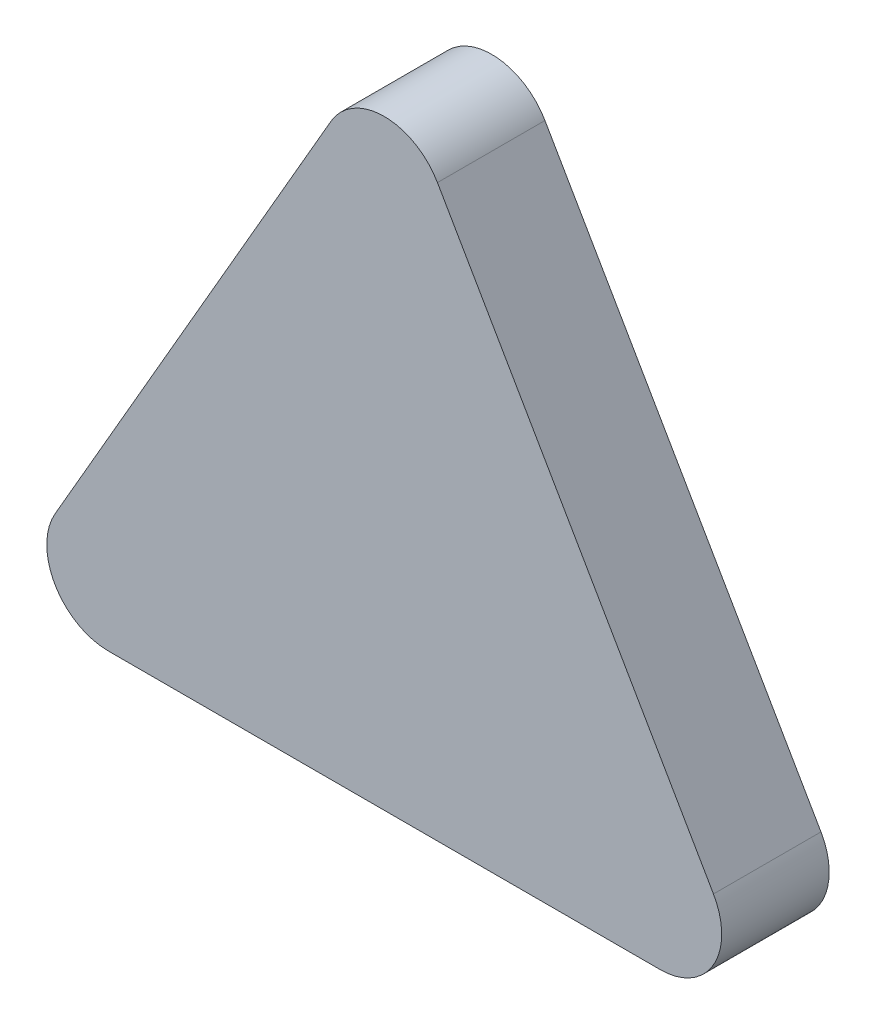
SolidWorks part; units mm, degrees
ref_plane "Plan de face" through (0, 0, 0) normal (0, 0, 1) x (1, 0, 0)
ref_plane "Plan de dessus" through (0, 0, 0) normal (0, 1, 0) x (1, 0, 0)
ref_plane "Plan de droite" through (0, 0, 0) normal (1, 0, 0) x (0, 0, -1)
sketch "Esquisse1" plane through (0, 0, 0) normal (0, 0, 1) x (1, 0, 0)
  line L0 (-12.45, 0) -> (12.45, 0)
  line L1 (12.45, 0) -> (0, 21.564)
  line L2 (0, 21.564) -> (-12.45, 0)
  dimension "D1" = 24.9
extrude "Boss.-Extru.1" add sketch "Esquisse1" along normal blind 3.5
sketch "Esquisse2" plane through (0, 0, 0) normal (0, 0, -1) x (-1, 0, 0)
  line L0 (0, 5.8748) -> (0, 0) construction
  line L1 (-2, 7.8748) -> (2, 7.8748)
  line L2 (-2, 7.8748) -> (-2, 3.8748)
  line L3 (-2, 3.8748) -> (2, 3.8748)
  line L4 (2, 7.8748) -> (2, 3.8748)
  line L5 (-2, 7.8748) -> (2, 3.8748) construction
  line L6 (-2, 3.8748) -> (2, 7.8748) construction
  line L7 (-12.84, -0.2252) -> (-12.45, 0) construction
  line L8 (-12.84, -0.2252) -> (12.84, -0.2252) construction
  line L9 (12.84, -0.2252) -> (0, 22.0144) construction
  line L10 (0, 22.0144) -> (-12.84, -0.2252) construction
  line L11 (12.45, 0) -> (-12.45, 0) construction
  line L12 (-12.45, 0) -> (0, 21.564) construction
  line L13 (0, 21.564) -> (12.45, 0) construction
  line L14 (0, 22.0144) -> (0, 21.564) construction
  line L17 (12.45, 0) -> (12.84, -0.2252) construction
  point P0 (0, 5.8748)
  point P18 (0, -0.2252)
  dimension "D1" = 4
  dimension "D2" = 25.68
  dimension "6.1" = 6.1
extrude "Enlèv. mat.-Extru.1" cut sketch "Esquisse2" against normal offset from surface (2.9 mm away) 0.6 contours L1 L4 L3 L2 up to face at (0, 7.188, 3.5)
fillet "Congé1" radius 2 3 edges at (12.45, 0, 1.75) (-12.45, 0, 1.75) (0, 21.564, 1.75)
